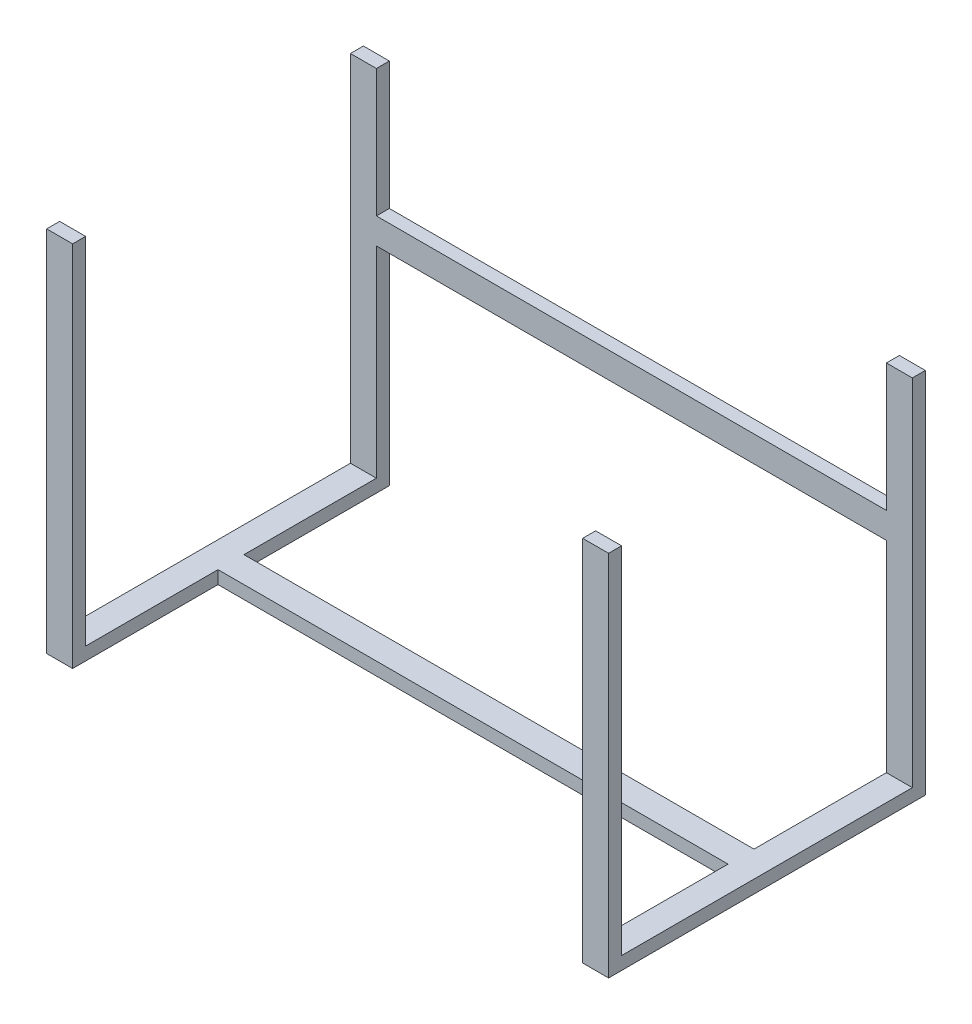
SolidWorks part; units mm, degrees
ref_plane "Front Plane" through (0, 0, 0) normal (0, 0, 1) x (1, 0, 0)
ref_plane "Top Plane" through (0, 0, 0) normal (0, 1, 0) x (1, 0, 0)
ref_plane "Right Plane" through (0, 0, 0) normal (1, 0, 0) x (0, 0, -1)
sketch "Sketch1" plane through (0, 0, 0) normal (1, 0, 0) x (0, 0, -1)
  line L0 (0, 720) -> (0, 0)
  line L1 (0, 0) -> (-620, 0)
  line L2 (-620, 0) -> (-620, 720)
  line L3 (-620, 720) -> (-594.6, 720)
  line L4 (-594.6, 720) -> (-594.6, 25.4)
  line L5 (-594.6, 25.4) -> (-25.4, 25.4)
  line L6 (-25.4, 25.4) -> (-25.4, 720)
  line L7 (-25.4, 720) -> (0, 720)
  dimension "D1" = 25.4
  dimension "D2" = 25.4
  dimension "D3" = 25.4
  dimension "D4" = 720
  dimension "D5" = 620
extrude "Boss-Extrude1" add sketch "Sketch1" along normal blind 50.8
sketch "Sketch2" plane through (50.8, 0, 0) normal (1, 0, 0) x (0, 0, -1)
  line L0 (-25.4, 25.4) -> (-594.6, 25.4) construction
  line L1 (-335.4, 25.4) -> (-284.6, 25.4)
  line L2 (-335.4, 25.4) -> (-335.4, 0)
  line L3 (-335.4, 0) -> (-284.6, 0)
  line L4 (-284.6, 25.4) -> (-284.6, 0)
  line L5 (-620, 0) -> (0, 0) construction
  line L6 (-310, 0) -> (-310, 25.4) construction
  line L8 (-310, 25.4) -> (-310, 0) construction
  dimension "D1" = 50.8
extrude "Boss-Extrude2" add sketch "Sketch2" along normal blind 499.2
mirror "Mirror1" about plane through (550, 0, 0) normal (1, 0, 0) of "Boss-Extrude1", "Boss-Extrude2"
sketch "Sketch3" plane through (50.8, 0, 0) normal (1, 0, 0) x (0, 0, -1)
  line L0 (-25.4, 720) -> (-25.4, 25.4) construction
  line L1 (-25.4, 470) -> (0, 470)
  line L2 (-25.4, 470) -> (-25.4, 419.2)
  line L3 (-25.4, 419.2) -> (0, 419.2)
  line L4 (0, 470) -> (0, 419.2)
  line L5 (0, 0) -> (0, 720) construction
  line L6 (0, 720) -> (-25.4, 720) construction
  dimension "D1" = 50.8
  dimension "D2" = 250
extrude "Boss-Extrude3" add sketch "Sketch3" along normal up to surface (998.4 mm away) up to face at (1049.2, 248.4667, 103.3333)
